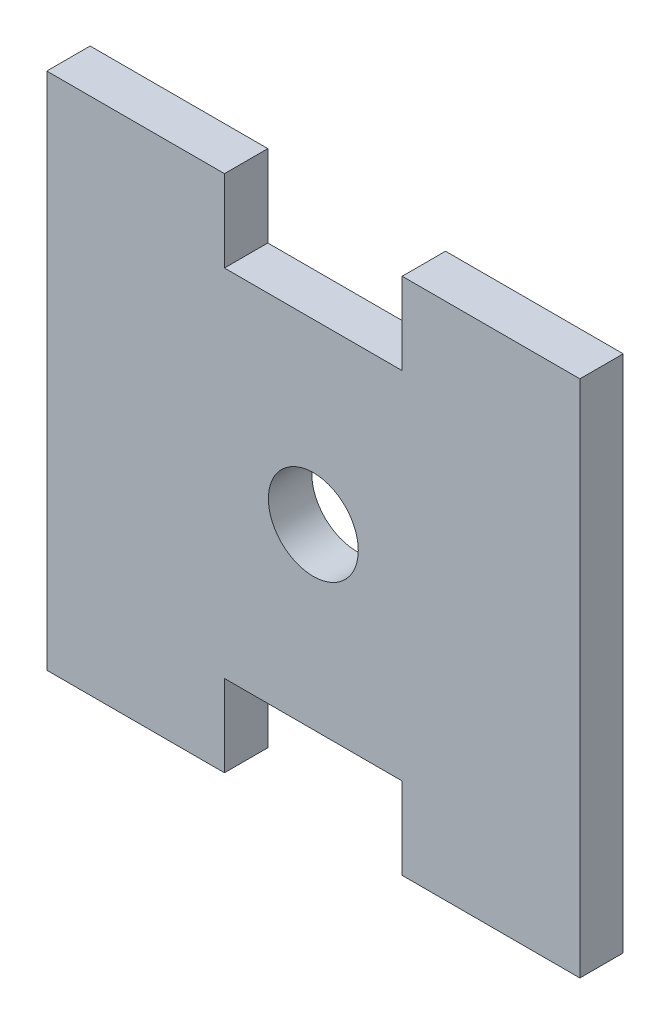
SolidWorks part; units mm, degrees
ref_plane "Front Plane" through (0, 0, 0) normal (0, 0, 1) x (1, 0, 0)
ref_plane "Top Plane" through (0, 0, 0) normal (0, 1, 0) x (1, 0, 0)
ref_plane "Right Plane" through (0, 0, 0) normal (1, 0, 0) x (0, 0, -1)
sketch "Sketch1" plane through (0, 0, 0) normal (0, 0, 1) x (1, 0, 0)
  line L0 (0, 12.7) -> (0, -12.7) construction
  line L1 (-6.35, -12.7) -> (6.35, -12.7)
  line L2 (-19.05, -12.7) -> (-19.05, 12.7)
  line L3 (-6.35, 12.7) -> (6.35, 12.7)
  line L4 (19.05, -12.7) -> (19.05, 12.7)
  line L5 (-19.05, -12.7) -> (19.05, 12.7) construction
  line L6 (-19.05, 12.7) -> (19.05, -12.7) construction
  line L7 (-19.05, 18.542) -> (-6.35, 18.542)
  line L8 (-19.05, 18.542) -> (-19.05, 12.7)
  line L9 (19.05, 18.542) -> (6.35, 12.7) construction
  line L10 (-6.35, 18.542) -> (-6.35, 12.7)
  line L11 (-19.05, 18.542) -> (-6.35, 12.7) construction
  line L12 (-19.05, 12.7) -> (-6.35, 18.542) construction
  line L13 (19.05, 12.7) -> (6.35, 18.542) construction
  line L14 (19.05, 18.542) -> (19.05, 12.7)
  line L15 (6.35, 18.542) -> (6.35, 12.7)
  line L16 (19.05, 18.542) -> (6.35, 18.542)
  line L17 (19.05, 0) -> (-19.05, 0) construction
  line L18 (-19.05, -18.542) -> (-19.05, -12.7)
  line L19 (-6.35, -18.542) -> (-6.35, -12.7)
  line L20 (-19.05, -12.7) -> (-6.35, -18.542) construction
  line L21 (-19.05, -18.542) -> (-6.35, -12.7) construction
  line L22 (-6.35, -12.7) -> (6.35, -12.7)
  line L23 (19.05, -18.542) -> (6.35, -12.7) construction
  line L24 (19.05, -12.7) -> (6.35, -18.542) construction
  line L25 (6.35, -18.542) -> (6.35, -12.7)
  line L26 (19.05, -18.542) -> (19.05, -12.7)
  line L27 (19.05, -18.542) -> (6.35, -18.542)
  line L28 (-19.05, -18.542) -> (-6.35, -18.542)
  circle A0 centre (0, 0) radius 3.2131
  point P0 (0, 0)
  point P8 (-12.7, 15.621)
  point P17 (12.7, 15.621)
  point P26 (12.7, -15.621)
  point P27 (-12.7, -15.621)
  dimension "D3" = 6.4262
  dimension "D1" = 25.4
  dimension "D2" = 38.1
  dimension "D4" = 5.842
  dimension "D5" = 12.7
extrude "Boss-Extrude1" add sketch "Sketch1" along normal blind 3.0988 contours L18 L28 L19 L1 L25 L27 L26 L4 L14 L16 L15 L3 L10 L7 L8 L2 A0
